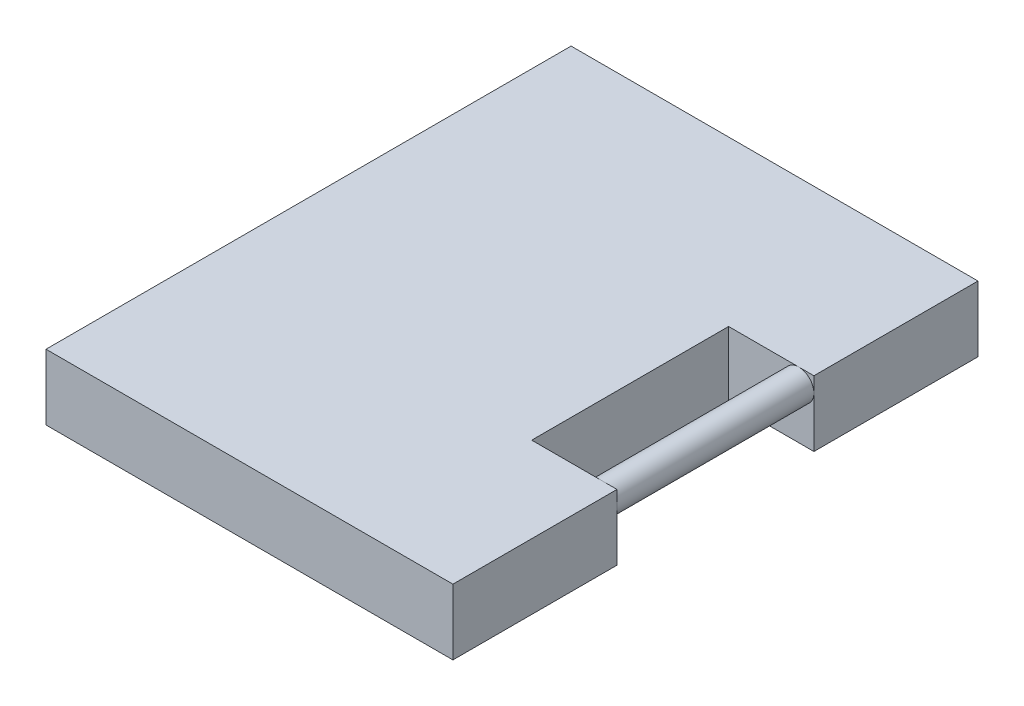
SolidWorks part; units mm, degrees
ref_plane "Front Plane" through (0, 0, 0) normal (0, 0, 1) x (1, 0, 0)
ref_plane "Top Plane" through (0, 0, 0) normal (0, 1, 0) x (1, 0, 0)
ref_plane "Right Plane" through (0, 0, 0) normal (1, 0, 0) x (0, 0, -1)
sketch "Sketch1" plane through (0, 0, 0) normal (0, 1, 0) x (1, 0, 0)
  line L0 (155, -200) -> (155, -75)
  line L1 (-155, -200) -> (155, -200)
  line L2 (-155, -200) -> (-155, 200)
  line L3 (-155, 200) -> (155, 200)
  line L5 (-155, -200) -> (155, 200) construction
  line L6 (-155, 200) -> (155, -200) construction
  line L7 (155, -75) -> (90, -75)
  line L8 (90, -75) -> (90, 75)
  line L9 (90, 75) -> (155, 75)
  line L10 (155, 75) -> (155, 200)
  point P0 (0, 0)
  dimension "D1" = 400
  dimension "D2" = 310
  dimension "D3" = 125
  dimension "D4" = 125
  dimension "D5" = 65
extrude "Boss-Extrude1" add sketch "Sketch1" along normal blind 50
sketch "Sketch2" plane through (0, 0, -75) normal (0, 0, 1) x (1, 0, 0)
  line L0 (90, 50) -> (155, 50) construction
  line L1 (155, 50) -> (155, 0) construction
  circle A0 centre (143.5, 38.5) radius 11.5
  dimension "D1" = 23
extrude "Boss-Extrude2" add sketch "Sketch2" along normal up to surface (150 mm away) up to face at (122.5, 25, 75)
